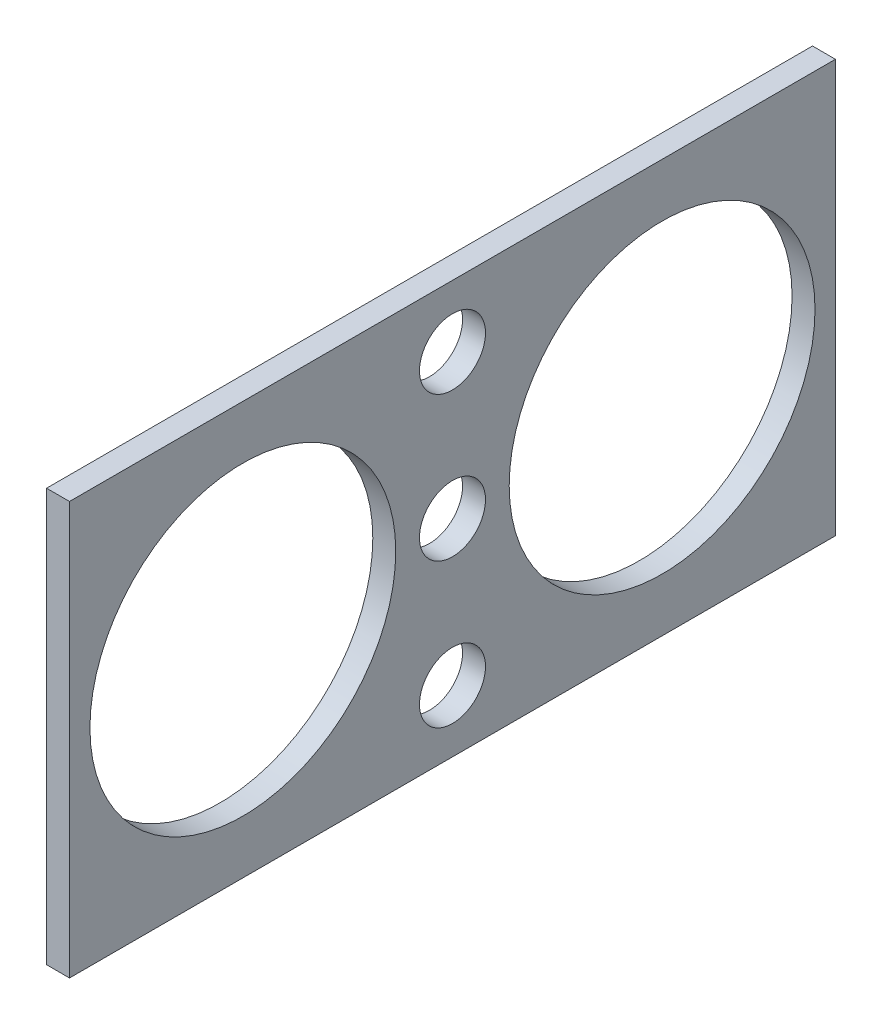
SolidWorks part; units mm, degrees
ref_plane "Front Plane" through (0, 0, 0) normal (0, 0, 1) x (1, 0, 0)
ref_plane "Top Plane" through (0, 0, 0) normal (0, 1, 0) x (1, 0, 0)
ref_plane "Right Plane" through (0, 0, 0) normal (1, 0, 0) x (0, 0, -1)
sketch "Sketch2" plane through (0, 0, 0) normal (1, 0, 0) x (0, 0, -1)
  line L0 (0, 0) -> (47.1399, 0)
  line L1 (47.1399, 0) -> (47.1399, 25.4)
  line L2 (47.1399, 25.4) -> (0, 25.4)
  line L3 (0, 25.4) -> (0, 0)
  line L4 (23.5699, 12.7) -> (23.5699, 3.81) construction
  line L5 (0, 12.7) -> (10.668, 12.7) construction
  line L6 (23.5699, 12.7) -> (23.5699, 21.59) construction
  circle A0 centre (23.5699, 21.59) radius 2.032
  circle A1 centre (23.5699, 12.7) radius 2.032
  circle A2 centre (23.5699, 3.81) radius 2.032
  circle A3 centre (10.668, 12.7) radius 9.411
  circle A4 centre (36.4719, 12.7) radius 9.411
extrude "Boss-Extrude1" add sketch "Sketch2" against normal blind 1.4122
